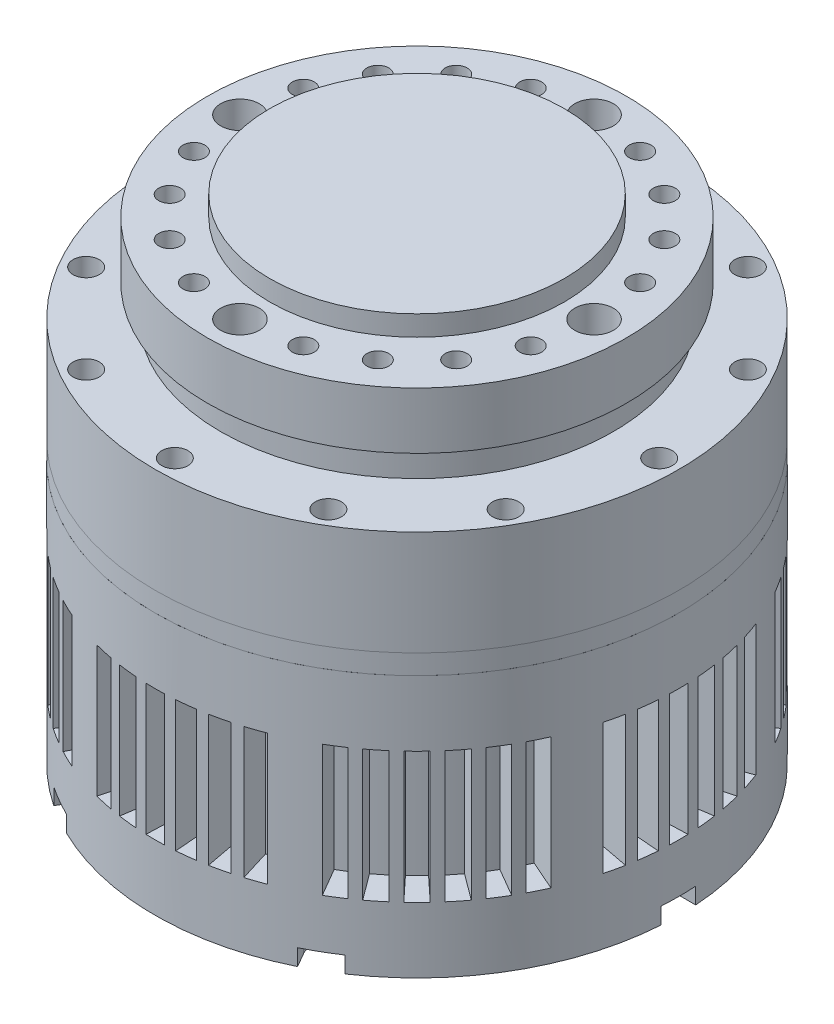
SolidWorks part; units mm, degrees
ref_plane "Front Plane" through (0, 0, 0) normal (0, 0, 1) x (1, 0, 0)
ref_plane "Top Plane" through (0, 0, 0) normal (0, 1, 0) x (1, 0, 0)
ref_plane "Right Plane" through (0, 0, 0) normal (1, 0, 0) x (0, 0, -1)
sketch "Sketch1" plane through (0, 0, 0) normal (0, 1, 0) x (1, 0, 0)
  circle A0 centre (0, 0) radius 40
  dimension "D1" = 80
extrude "Boss-Extrude1" add sketch "Sketch1" along normal blind 16 contours A0
sketch "Sketch2" plane through (0, 16, 0) normal (0, 1, 0) x (1, 0, 0)
  circle A0 centre (0, 37) radius 2
  dimension "D1" = 4
  dimension "D2" = 37
extrude "Cut-Extrude1" cut sketch "Sketch2" against normal blind 5
pattern_circular "CirPattern1" count 12 over 360 about axis through (0, 0, 0) along (0, 1, 0) of "Cut-Extrude1"
sketch "Sketch3" plane through (0, 0, 0) normal (0, -1, 0) x (1, 0, 0)
  circle A0 centre (0, 0) radius 40
  circle A1 centre (0, 0) radius 40 construction
extrude "Boss-Extrude2" add sketch "Sketch3" along normal blind 3 separate body
sketch "Sketch4" plane through (0, -3, 0) normal (0, -1, 0) x (1, 0, 0)
  circle A0 centre (0, 0) radius 40
  circle A1 centre (0, 0) radius 40 construction
extrude "Boss-Extrude3" add sketch "Sketch4" along normal blind 40 separate body
sketch "Sketch5" plane through (0, -43, 0) normal (0, -1, 0) x (1, 0, 0)
  line L0 (-10.2297, 38.6698) -> (-8.951, 33.8361)
  line L1 (-6.5128, 34.3887) -> (-7.4432, 39.3014)
  line L2 (-5.1323, 34.6217) -> (-5.8655, 39.5676)
  line L3 (-2.6478, 34.8997) -> (-3.0261, 39.8854)
  line L4 (-1.4286, 39.9745) -> (-1.25, 34.9777)
  line L5 (1.4286, 39.9745) -> (1.25, 34.9777)
  line L6 (2.6478, 34.8997) -> (3.0261, 39.8854)
  line L7 (5.1323, 34.6217) -> (5.8655, 39.5676)
  line L8 (7.4432, 39.3014) -> (6.5128, 34.3887)
  line L9 (10.2297, 38.6698) -> (8.951, 33.8361)
  line L10 (14.4669, 37.2922) -> (12.6585, 32.6307)
  line L11 (11.768, 38.2298) -> (10.297, 33.451)
  line L12 (-6.978, 36.845) -> (-5.4989, 37.0946) construction
  line L13 (-2.837, 37.3925) -> (-1.3393, 37.4761) construction
  line L14 (1.3393, 37.4761) -> (2.837, 37.3925) construction
  line L15 (5.4989, 37.0946) -> (6.978, 36.845) construction
  line L16 (9.5903, 36.2529) -> (11.0325, 35.8404) construction
  line L17 (-9.5903, 36.2529) -> (-6.978, 36.845) construction
  line L18 (-5.4989, 37.0946) -> (-2.837, 37.3925) construction
  line L19 (-1.3393, 37.4761) -> (1.3393, 37.4761) construction
  line L20 (2.837, 37.3925) -> (5.4989, 37.0946) construction
  line L21 (6.978, 36.845) -> (9.5903, 36.2529) construction
  line L22 (11.0325, 35.8404) -> (13.5627, 34.9614) construction
  line L23 (28.7562, 44.6999) -> (-40.4872, 34.4353) construction
  line L24 (-5.8655, 39.5676) -> (0, 0) construction
  arc A0 (12.6585, 32.6307) -> (10.297, 33.451) centre (0, 0) ccw
  circle A1 centre (0, 0) radius 40 construction
  arc A3 (14.4669, 37.2922) -> (11.768, 38.2298) centre (0, 0) ccw
  arc A5 (-3.0261, 39.8854) -> (-5.8655, 39.5676) centre (0, 0) ccw
  arc A6 (1.4286, 39.9745) -> (-1.4286, 39.9745) centre (0, 0) ccw
  arc A7 (5.8655, 39.5676) -> (3.0261, 39.8854) centre (0, 0) ccw
  arc A8 (10.2297, 38.6698) -> (7.4432, 39.3014) centre (0, 0) ccw
  arc A9 (8.951, 33.8361) -> (6.5128, 34.3887) centre (0, 0) ccw
  arc A10 (5.1323, 34.6217) -> (2.6478, 34.8997) centre (0, 0) ccw
  arc A11 (1.25, 34.9777) -> (-1.25, 34.9777) centre (0, 0) ccw
  arc A12 (-2.6478, 34.8997) -> (-5.1323, 34.6217) centre (0, 0) ccw
  arc A13 (-6.5128, 34.3887) -> (-8.951, 33.8361) centre (0, 0) ccw
  arc A14 (-7.4432, 39.3014) -> (-5.8655, 39.5676) centre (0, 0) cw construction
  arc A15 (-1.4286, 39.9745) -> (-3.0261, 39.8854) centre (0, 0) ccw construction
  arc A16 (3.0261, 39.8854) -> (1.4286, 39.9745) centre (0, 0) ccw construction
  arc A17 (7.4432, 39.3014) -> (5.8655, 39.5676) centre (0, 0) ccw construction
  arc A18 (11.768, 38.2298) -> (10.2297, 38.6698) centre (0, 0) ccw construction
  arc A19 (-7.4432, 39.3014) -> (-10.2297, 38.6698) centre (0, 0) ccw
  point P15 (-5.8655, 39.5676)
  point P50 (0, 35)
  dimension "D1" = 5
  dimension "D2" = 2.5
  dimension "D3" = 70
  dimension "D4" = 1.5
sketch "Sketch6" plane through (0, 16, 0) normal (0, 1, 0) x (1, 0, 0)
  circle A0 centre (0, 0) radius 40 construction
  circle A1 centre (0, 0) radius 30
  dimension "D1" = 80
  dimension "D2" = 10
extrude "Boss-Extrude4" add sketch "Sketch6" along normal blind 4.75 separate body
sketch "Sketch8" plane through (0, 20.75, 0) normal (0, 1, 0) x (1, 0, 0)
  circle A0 centre (0, 0) radius 32
  dimension "D1" = 64
extrude "Boss-Extrude5" add sketch "Sketch8" along normal blind 8.65 separate body
sketch "Sketch9" plane through (0, 29.4, 0) normal (0, 1, 0) x (1, 0, 0)
  circle A0 centre (0, 0) radius 22.5
  dimension "D1" = 45
extrude "Boss-Extrude6" add sketch "Sketch9" along normal blind 3.1
sketch "Sketch10" plane through (0, 29.4, 0) normal (0, 1, 0) x (1, 0, 0)
  circle A40 centre (0, 27.05) radius 2.95
  dimension "D1" = 27.05
  dimension "D2" = 5.9
extrude "Cut-Extrude5" cut sketch "Sketch10" against normal blind 7
pattern_circular "CirPattern3" count 4 over 360 about axis through (0, 0, 0) along (0, 1, 0) of "Cut-Extrude5"
sketch "Sketch14" plane through (0, 29.4, 0) normal (0, 1, 0) x (1, 0, 0)
  line L0 (25.7261, 8.3589) -> (25.7261, 0) construction
  line L1 (25.7261, 0) -> (0, 0) construction
  line L2 (0, 0) -> (25.7261, 8.3589) construction
  circle A0 centre (25.7261, 8.3589) radius 1.675
  circle A1 centre (0, 0) radius 27.05 construction
  dimension "D2" = 3.35
  dimension "D1" = 18
extrude "Cut-Extrude6" cut sketch "Sketch14" against normal blind 7
pattern_circular "CirPattern4" count 20 over 360 about axis through (0, 0, 0) along (0, 1, 0) skipping 4, 9, 14, 19 of "Cut-Extrude6"
sketch "Sketch16" plane through (0, -43, 0) normal (0, -1, 0) x (1, 0, 0)
  line L0 (-18.6667, 32.3316) -> (18.6667, 32.3316) construction
  line L1 (-16, 32.3316) -> (16, 32.3316) construction
  line L2 (-18.6667, 32.3316) -> (0, 0) construction
  line L3 (0, 0) -> (18.6667, 32.3316) construction
  line L4 (20.9761, 30.9983) -> (22.2649, 33.2306)
  line L5 (16.3573, 33.6649) -> (17.6461, 35.8973)
  circle A0 centre (-18.6667, 32.3316) radius 2.6667 construction
  circle A1 centre (0, 0) radius 40 construction
  arc A2 (16.3573, 33.6649) -> (20.9761, 30.9983) centre (18.6667, 32.3316) ccw construction
  arc A3 (16.3573, 33.6649) -> (20.9761, 30.9983) centre (18.6667, 32.3316) ccw
  arc A4 (17.6461, 35.8973) -> (22.2649, 33.2306) centre (0, 0) cw
  point P8 (0, 32.3316)
  dimension "D3" = 5.3333
  dimension "D1" = 32
  dimension "D2" = 60
  dimension "D4" = 37.3333
extrude "Cut-Extrude8" cut sketch "Sketch16" against normal blind 2.5
pattern_circular "CirPattern5" count 6 over 360 about axis through (0, 0, 0) along (0, 1, 0) of "Cut-Extrude8"
extrude "Cut-Extrude9" cut sketch "Sketch5" against normal blind 20 from offset 10 offset against normal yes
pattern_circular "CirPattern6" count 8 over 360 about axis through (0, 0, 0) along (0, 1, 0) of "Cut-Extrude9"
sketch "Sketch17" plane through (0, 29.4, 0) normal (0, 1, 0) x (1, 0, 0)
  circle A0 centre (0, 0) radius 27.05 construction
  circle A1 centre (15.8996, 21.8839) radius 1.675
  circle A2 centre (15.8996, 21.8839) radius 1.675 construction
equation "\"small black ring h\"= 4.75mm"
equation "\"D1@Boss-Extrude4\"=\"small black ring h\""
equation "\"D1@Boss-Extrude5\"=13.4-\"small black ring h\""
